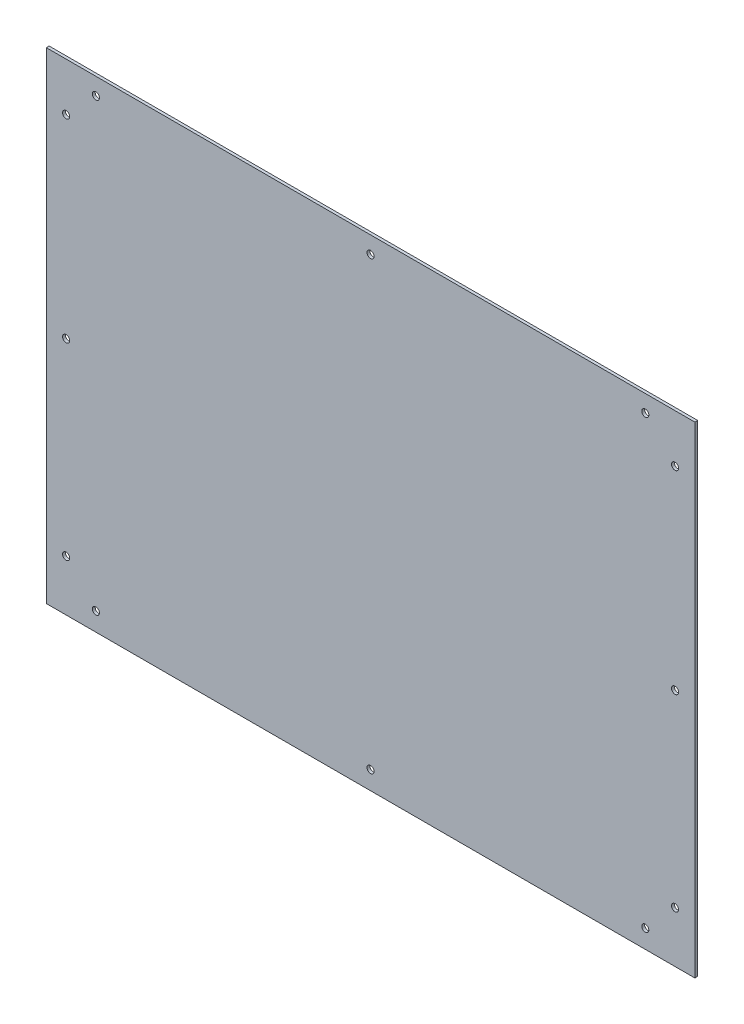
SolidWorks part; units mm, degrees
material "1345 Alloy"
ref_plane "Front Plane" through (0, 0, 0) normal (0, 0, 1) x (1, 0, 0)
ref_plane "Top Plane" through (0, 0, 0) normal (0, 1, 0) x (1, 0, 0)
ref_plane "Right Plane" through (0, 0, 0) normal (1, 0, 0) x (0, 0, -1)
sketch "Sketch1" plane through (0, 0, 0) normal (0, 0, 1) x (1, 0, 0)
  line L1 (-229, 169) -> (229, 169)
  line L2 (-229, 169) -> (-229, -169)
  line L3 (-229, -169) -> (229, -169)
  line L4 (229, 169) -> (229, -169)
  line L5 (-229, 169) -> (229, -169) construction
  line L6 (-229, -169) -> (229, 169) construction
  point P0 (0, 0)
  dimension "D1" = 458
  dimension "D2" = 338
extrude "Boss-Extrude1" add sketch "Sketch1" along normal blind 2
sketch "Sketch2" plane through (0, 0, 2) normal (0, 0, 1) x (1, 0, 0)
  line L4 (-194.0026, -156) -> (193.9974, -156) construction
  line L5 (-215, 137) -> (-215, -133) construction
  line L6 (215, 137) -> (215, -133) construction
  line L8 (194, 159) -> (194, 169) construction
  line L11 (-229, -169) -> (229, -169) construction
  line L12 (229, 0) -> (215, 0) construction
  line L14 (229, 169) -> (-229, 169) construction
  circle A0 centre (-194, 159) radius 2.5
  circle A1 centre (-194.0026, -156) radius 2.5
  circle A2 centre (193.9974, -156) radius 2.5
  circle A3 centre (194, 159) radius 2.5
  circle A4 centre (-215, 0) radius 2.5
  circle A5 centre (-215, -133) radius 2.5
  circle A6 centre (-215, 137) radius 2.5
  circle A7 centre (215, 0) radius 2.5
  circle A8 centre (215, -133) radius 2.5
  circle A9 centre (215, 137) radius 2.5
  circle A10 centre (0, 159) radius 2.5
  circle A11 centre (-0.0026, -156) radius 2.5
  dimension "D3" = 5
  dimension "D6" = 5
  dimension "D7" = 5
  dimension "D8" = 5
  dimension "D13" = 5
  dimension "D14" = 5
  dimension "D15" = 5
  dimension "D19" = 5
  dimension "D20" = 5
  dimension "D4" = 215
  dimension "D5" = 215
  dimension "D9" = 13
  dimension "D11" = 36
  dimension "D18" = 13
  dimension "D21" = 194
  dimension "D24" = 194
  dimension "D26" = 32
  dimension "D27" = 137
extrude "Cut-Extrude1" cut sketch "Sketch2" against normal through all
sketch "Sketch3" plane through (0, 0, 2) normal (0, 0, 1) x (1, 0, 0)
  line L1 (-229, 169) -> (229, 169)
  line L2 (-229, 169) -> (-229, 171)
  line L3 (-229, 171) -> (229, 171)
  line L4 (229, 169) -> (229, 171)
  dimension "D1" = 458
  dimension "D2" = 2
extrude "Boss-Extrude2" add sketch "Sketch3" against normal through all
